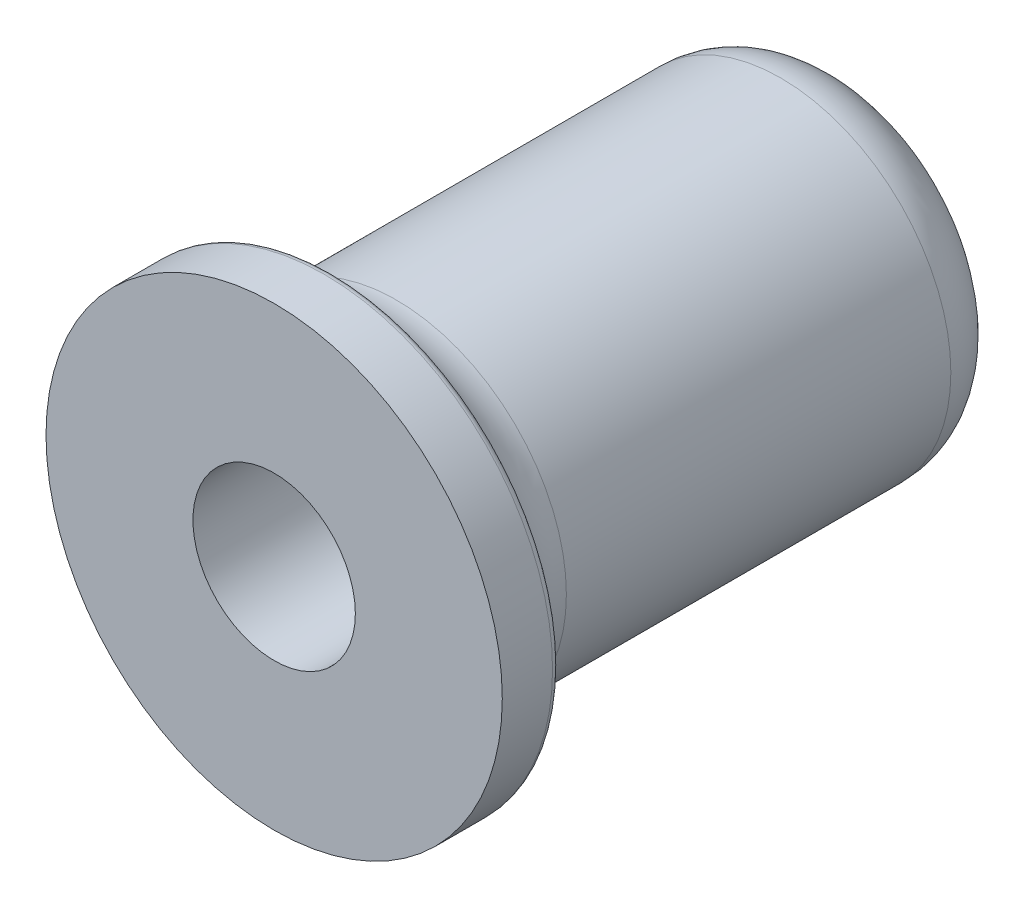
SolidWorks part; units mm, degrees
ref_plane "Alzado" through (0, 0, 0) normal (0, 0, 1) x (1, 0, 0)
ref_plane "Planta" through (0, 0, 0) normal (0, 1, 0) x (1, 0, 0)
ref_plane "Vista lateral" through (0, 0, 0) normal (1, 0, 0) x (0, 0, -1)
sketch "Croquis1" plane through (0, 0, 0) normal (0, 1, 0) x (1, 0, 0)
  line L1 (0, 0) -> (5.9, 0)
  line L2 (0, 0) -> (0, 14.8)
  line L3 (0, 14.8) -> (5.9, 14.8)
  line L4 (5.9, 0) -> (5.9, 14.8)
  dimension "D1" = 14.8
  dimension "D2" = 5.9
revolve "Revolución1" add sketch "Croquis1" angle 360 about L2
sketch "Croquis2" plane through (0, 0, 0) normal (0, 0, 1) x (1, 0, 0)
  circle A0 centre (0, 0) radius 2.1
  circle A1 centre (0, 0) radius 5.9 construction
  dimension "D1" = 3.8
extrude "Cortar-Extruir2" cut sketch "Croquis2" against normal blind 13 contours A0
sketch "Croquis13" plane through (0, 0, -14.8) normal (0, 0, -1) x (-1, 0, 0)
  circle A0 centre (0, 0) radius 2.7
  dimension "D1" = 5.4
sketch "Croquis18" plane through (0, 0, 0) normal (0, 1, 0) x (1, 0, 0)
sketch "Croquis19" plane through (0, 0, 0) normal (0, 1, 0) x (1, 0, 0)
sketch "Croquis20" plane through (0, 0, 0) normal (0, 1, 0) x (1, 0, 0)
sketch "Croquis23" plane through (0, 0, 0) normal (0, 1, 0) x (1, 0, 0)
  line L0 (0, 0) -> (0, 1.5) construction
  line L2 (0, 1.5) -> (0, 14.8) construction
  line L3 (2.7, 14.8) -> (-2.7, 14.8) construction
  line L4 (5.9, 0) -> (5.9, 14.8) construction
  line L5 (5.9, 1.5) -> (4.4, 1.5)
  line L6 (5.9, 1.5) -> (5.9, 14.8)
  line L7 (5.9, 14.8) -> (4.4, 14.8)
  line L8 (4.4, 1.5) -> (4.4, 14.8)
  line L9 (5.9, 14.8) -> (-5.9, 14.8) construction
  dimension "D1" = 1.5
  dimension "D2" = 1.5
revolve "Cortar-Revolución2" cut sketch "Croquis23" angle 360 about L2
fillet "Redondeo1" radius 0.2 1 edges at (5.9, 0, -1.5)
fillet "Redondeo2" radius 1.7 1 edges at (4.4, 0, -14.8)
fillet "Redondeo3" radius 1.7 1 edges at (4.4, 0, -1.5)
